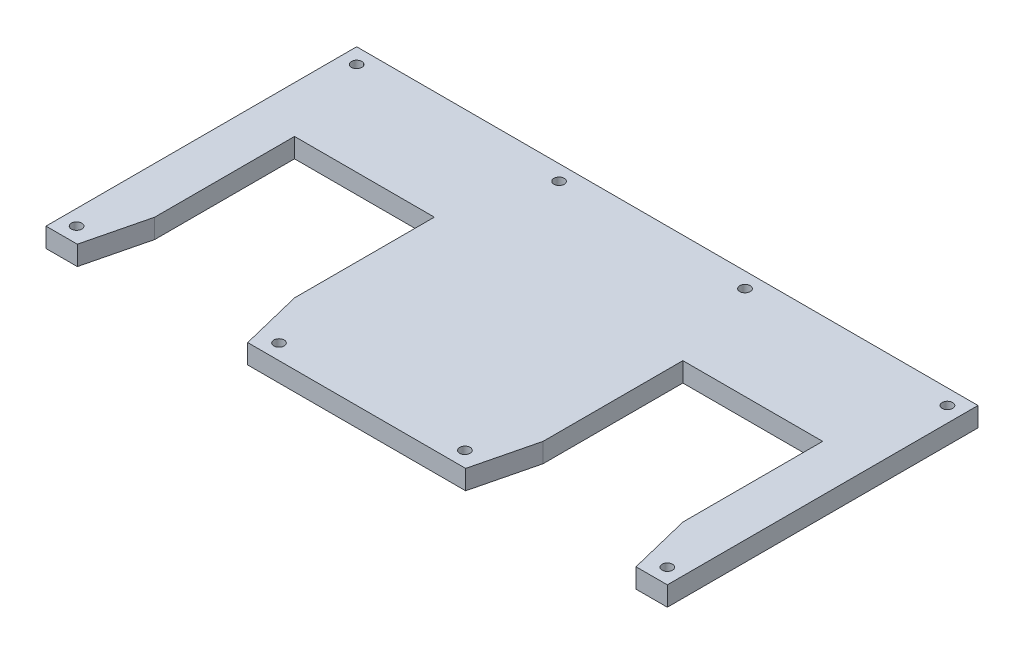
SolidWorks part; units mm, degrees
ref_plane "Front Plane" through (0, 0, 0) normal (0, 0, 1) x (1, 0, 0)
ref_plane "Top Plane" through (0, 0, 0) normal (0, 1, 0) x (1, 0, 0)
ref_plane "Right Plane" through (0, 0, 0) normal (1, 0, 0) x (0, 0, -1)
sketch "Sketch1" plane through (0, 0, 0) normal (0, 1, 0) x (1, 0, 0)
  line L0 (15.24, 20.32) -> (15.24, 66.04)
  line L1 (0, 0) -> (10.24, 0)
  line L2 (0, 0) -> (0, 101.6)
  line L3 (0, 101.6) -> (76.2, 101.6)
  line L4 (76.2, 0) -> (76.2, 101.6)
  line L5 (15.24, 66.04) -> (60.96, 66.04)
  line L6 (60.96, 66.04) -> (60.96, 20.32)
  line L7 (65.96, 0) -> (76.2, 0)
  line L8 (10.24, 0) -> (15.24, 20.32)
  line L9 (60.96, 20.32) -> (65.96, 0)
  point P5 (15.24, 0)
  point P9 (60.96, 0)
  dimension "D1" = 101.6
  dimension "D2" = 15.24
  dimension "D3" = 66.04
  dimension "D4" = 15.24
  dimension "D5" = 20.32
  dimension "D6" = 5
  dimension "D7" = 20.32
  dimension "D8" = 5
  dimension "D9" = 76.2
extrude "Boss-Extrude1" add sketch "Sketch1" along normal blind 6.35
sketch "Sketch2" plane through (0, 6.35, 0) normal (0, 1, 0) x (1, 0, 0)
  line L0 (38.1, 0) -> (38.1, 68.5972) construction
  line L1 (76.2, 0) -> (76.2, 101.6) construction
  line L2 (0, 50.8) -> (66.4895, 50.8) construction
  line L6 (0, 101.6) -> (0, 0) construction
  line L7 (76.2, 101.6) -> (0, 101.6) construction
  circle A0 centre (5, 96.6) radius 1.7
  circle A1 centre (71.2, 96.6) radius 1.7
  circle A2 centre (71.2, 5) radius 1.7
  circle A3 centre (5, 5) radius 1.7
  point P2 (33.2447, 50.8)
  point P3 (38.1, 34.2986)
  point P20 (76.2, 50.8)
  point P21 (38.1, 101.6)
  dimension "D1" = 3.4
  dimension "D2" = 5
  dimension "D3" = 5
extrude "Cut-Extrude1" cut sketch "Sketch2" against normal through all
ref_plane "Plane1" through (-25.4, 0, 0) normal (-1, 0, 0) x (0, 0, 1)
mirror "Mirror1" about plane through (-25.4, 0, 0) normal (-1, 0, 0) of bodies 102
sketch "Sketch3" plane through (-50.8, 0, 0) normal (1, 0, 0) x (0, 0, -1)
  line L1 (0, 0) -> (101.6, 0)
  line L2 (0, 0) -> (0, 6.35)
  line L3 (0, 6.35) -> (101.6, 6.35)
  line L4 (101.6, 0) -> (101.6, 6.35)
extrude "Boss-Extrude2" add sketch "Sketch3" along normal up to surface (50.8 mm away) up to face at (0, 3.175, -50.8)
